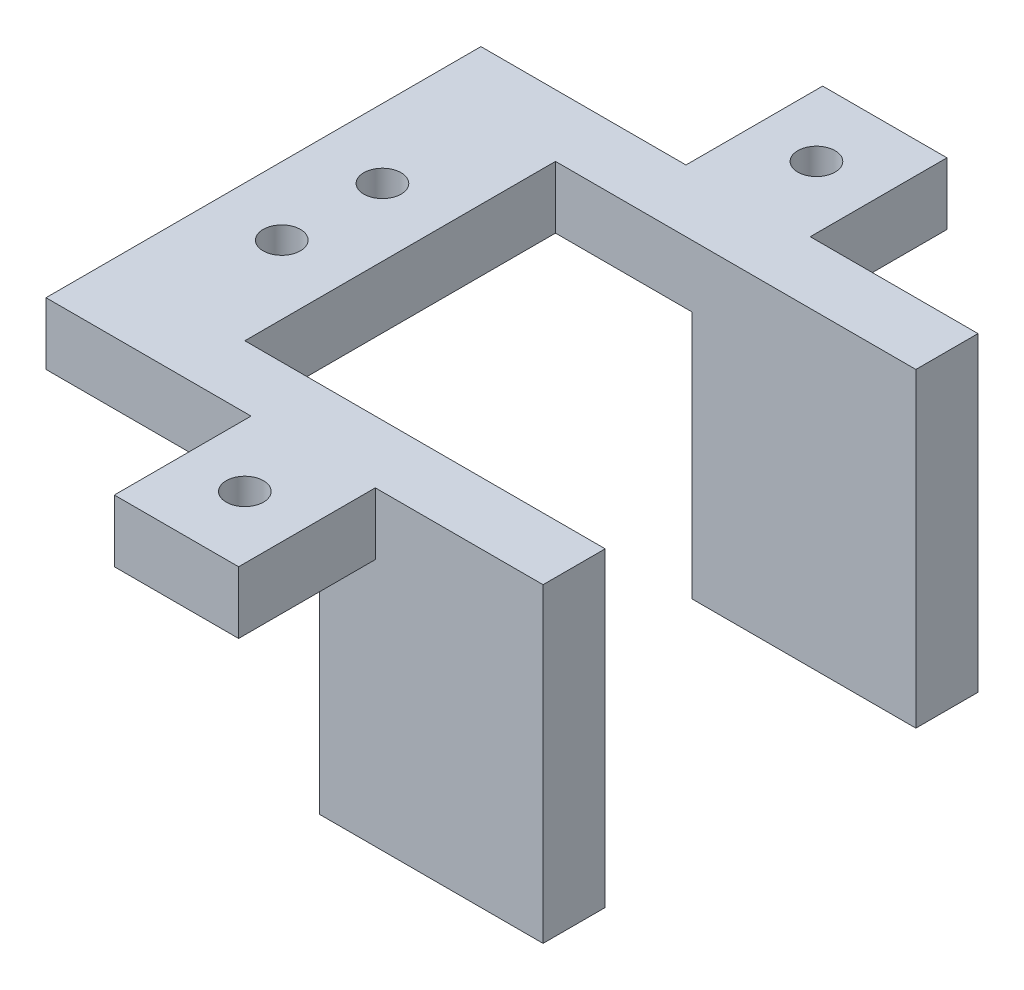
SolidWorks part; units mm, degrees
ref_plane "Front Plane" through (0, 0, 0) normal (0, 0, 1) x (1, 0, 0)
ref_plane "Top Plane" through (0, 0, 0) normal (0, 1, 0) x (1, 0, 0)
ref_plane "Right Plane" through (0, 0, 0) normal (1, 0, 0) x (0, 0, -1)
sketch "Sketch1" plane through (0, 0, 0) normal (0, 1, 0) x (1, 0, 0)
  line L0 (0, 0) -> (0, -2.5)
  line L1 (0, 0) -> (0, 2.5)
  line L3 (0, 0) -> (-1.8324, 0)
  line L5 (1.5, 3) -> (5.5, 3)
  line L6 (5.5, 3) -> (5.5, 0)
  line L7 (5.5, 0) -> (5.5, -3)
  line L8 (5.5, -3) -> (1.5, -3)
  line L10 (0, 4.5) -> (0, 8.5)
  line L11 (0, 8.5) -> (5.5, 8.5)
  line L12 (5.5, 8.5) -> (5.5, 3)
  line L13 (0, -8.5) -> (5.5, -8.5)
  line L14 (5.5, -8.5) -> (5.5, -3)
  line L15 (0, -8.5) -> (0, -4.5)
  line L16 (-1.5, -3) -> (-5.5, -3)
  line L17 (-5.5, -3) -> (-5.5, -8.5)
  line L18 (-5.5, -8.5) -> (0, -8.5)
  line L19 (-5.5, -3) -> (-5.5, 8.5)
  line L20 (-5.5, 8.5) -> (0, 8.5)
  circle A0 centre (0, 3) radius 1.5
  circle A1 centre (0, -3) radius 1.5
extrude "Boss-Extrude1" add sketch "Sketch1" along normal blind 5 contours L19 L20 L11 L12 L6 L7 L14 L13 L18 L17
sketch "Sketch3" plane through (0, 0, 8.5) normal (0, 0, 1) x (1, 0, 0)
  line L0 (-5.5, 5) -> (-5.5, 0)
  line L1 (-5.5, 0) -> (5.5, 0)
  line L2 (5.5, 0) -> (5.5, 5)
  line L3 (5.5, 5) -> (-5.5, 5)
extrude "Boss-Extrude2" add sketch "Sketch3" along normal blind 5
sketch "Sketch4" plane through (5.5, 0, 0) normal (1, 0, 0) x (0, 0, -1)
  line L0 (-13.5, 5) -> (-8.5, 5)
  line L1 (-13.5, 5) -> (8.5, 5) construction
  line L2 (-8.5, 5) -> (-8.5, 0)
  line L3 (8.5, 0) -> (-13.5, 0) construction
  line L4 (-8.5, 0) -> (-13.5, 0)
  line L5 (-13.5, 0) -> (-13.5, 5)
extrude "Boss-Extrude3" add sketch "Sketch4" along normal blind 21
sketch "Sketch5" plane through (0, 0, 0) normal (0, -1, 0) x (1, 0, 0)
  line L0 (26.5, 13.5) -> (16.5, 13.5)
  line L1 (-5.5, 13.5) -> (26.5, 13.5) construction
  line L2 (16.5, 13.5) -> (16.5, 8.5)
  line L3 (26.5, 8.5) -> (5.5, 8.5) construction
  line L4 (16.5, 8.5) -> (26.5, 8.5)
  line L5 (26.5, 8.5) -> (26.5, 13.5)
extrude "Boss-Extrude4" add sketch "Sketch5" along normal blind 20
sketch "Sketch6" plane through (0, 0, -8.5) normal (0, 0, -1) x (-1, 0, 0)
  line L0 (5.5, 5) -> (5.5, 0)
  line L1 (5.5, 0) -> (-5.5, 0)
  line L2 (-5.5, 0) -> (-5.5, 5)
  line L3 (-5.5, 5) -> (5.5, 5)
extrude "Boss-Extrude5" add sketch "Sketch6" along normal blind 5
sketch "Sketch7" plane through (5.5, 0, 0) normal (1, 0, 0) x (0, 0, -1)
  line L0 (13.5, 5) -> (8.5, 5)
  line L1 (-8.5, 5) -> (13.5, 5) construction
  line L2 (8.5, 5) -> (8.5, 0)
  line L3 (13.5, 0) -> (-8.5, 0) construction
  line L4 (8.5, 0) -> (13.5, 0)
  line L5 (13.5, 0) -> (13.5, 5)
extrude "Boss-Extrude6" add sketch "Sketch7" along normal blind 21
sketch "Sketch8" plane through (0, 0, 0) normal (0, -1, 0) x (-1, 0, 0)
  line L0 (-26.5, 8.5) -> (-16.5, 8.5)
  line L1 (-26.5, 8.5) -> (-5.5, 8.5) construction
  line L2 (-16.5, 8.5) -> (-16.5, 13.5)
  line L3 (-26.5, 13.5) -> (5.5, 13.5) construction
  line L4 (-16.5, 13.5) -> (-26.5, 13.5)
  line L5 (-26.5, 13.5) -> (-26.5, 8.5)
extrude "Boss-Extrude7" add sketch "Sketch8" along normal blind 20 contours L2 L4 L5 L0
sketch "Sketch11" plane through (0, 0, 8.5) normal (0, 0, -1) x (-1, 0, 0)
  line L0 (-26.5, -20) -> (-26.5, -15)
  line L1 (-26.5, -20) -> (-26.5, 5) construction
  line L2 (-26.5, -15) -> (-26.5, -10)
  line L3 (-26.5, -10) -> (-16.5, -10)
  line L4 (-16.5, -20) -> (-16.5, 0) construction
  line L5 (-16.5, -10) -> (-16.5, -15)
  line L6 (-16.5, -15) -> (-26.5, -15)
extrude "Boss-Extrude8" add sketch "Sketch11" along normal blind 3.5 contours L2 L3 L5 L6
sketch "Sketch12" plane through (0, 0, -8.5) normal (0, 0, 1) x (1, 0, 0)
  line L0 (26.5, -20) -> (26.5, -15)
  line L1 (26.5, 5) -> (26.5, -20) construction
  line L2 (26.5, -15) -> (26.5, -10)
  line L3 (26.5, -10) -> (16.5, -10)
  line L4 (16.5, -20) -> (16.5, 0) construction
  line L5 (16.5, -10) -> (16.5, -15)
  line L6 (16.5, -15) -> (26.5, -15)
extrude "Boss-Extrude9" add sketch "Sketch12" along normal blind 3.5 contours L2 L3 L5 L6
sketch "Sketch14" plane through (26.5, 0, 0) normal (1, 0, 0) x (0, 0, -1)
  line L4 (-6.3796, -12.8796) -> (-6.3796, -15)
  line L7 (-6.3796, -15) -> (-5, -15)
  line L8 (-6.3796, -12.8796) -> (-6.3796, -11.4398)
  line L10 (-6.3796, -11.4398) -> (-5, -11.4398)
  line L11 (-5, -15) -> (-5, -10) construction
  line L12 (-5, -15) -> (-8.5, -15) construction
  line L13 (-5, -15) -> (-5, -11.4398)
extrude "Cut-Extrude6" cut sketch "Sketch14" against normal blind 14.5 contours L4 L7 L13 L10 L8
sketch "Sketch16" plane through (26.5, 0, 0) normal (1, 0, 0) x (0, 0, -1)
  line L0 (-8.5, -15) -> (-7.4398, -15)
  line L2 (-6.3796, -15) -> (-8.5, -15) construction
  line L3 (-6.3796, -15) -> (-6.3796, -13)
  line L4 (-6.3796, -11.4398) -> (-6.3796, -15) construction
  line L5 (-6.3796, -13) -> (-8.5, -15)
extrude "Cut-Extrude8" cut sketch "Sketch16" against normal blind 14.5 and the other way through all contours L3 L5 L0
sketch "Sketch17" plane through (26.5, 0, 0) normal (1, 0, 0) x (0, 0, -1)
  line L0 (5, -10) -> (5, -11.44)
  line L1 (5, -15) -> (5, -10) construction
  line L2 (5, -11.44) -> (6.38, -11.44)
  line L3 (6.38, -11.44) -> (6.38, -15)
  line L4 (5, -15) -> (8.5, -15) construction
  line L5 (5, -11.44) -> (5, -15)
  line L6 (5, -15) -> (6.38, -15)
extrude "Cut-Extrude9" cut sketch "Sketch17" against normal blind 14.5 contours L2 L3 L6 L5
sketch "Sketch18" plane through (26.5, 0, 0) normal (1, 0, 0) x (0, 0, -1)
  line L0 (6.38, -13) -> (6.38, -15)
  line L1 (6.38, -11.44) -> (6.38, -15) construction
  line L2 (6.38, -13) -> (8.5, -15)
  line L3 (6.38, -15) -> (8.5, -15)
extrude "Cut-Extrude10" cut sketch "Sketch18" against normal blind 14.5 contours L2 L3 L0
sketch "草图1" plane through (0, 0, 13.5) normal (0, 0, 1) x (1, 0, 0)
  line L0 (26.5, 5) -> (34.5, 5)
  line L1 (26.5, 5) -> (26.5, -20)
  line L2 (26.5, -20) -> (34.5, -20)
  line L3 (34.5, -20) -> (34.5, 5)
extrude "凸台-拉伸1" add sketch "草图1" against normal blind 5
sketch "草图2" plane through (0, 0, -13.5) normal (0, 0, -1) x (-1, 0, 0)
  line L0 (-26.5, -20) -> (-34.5, -20)
  line L1 (-34.5, -20) -> (-34.5, 5)
  line L2 (-34.5, 5) -> (-26.5, 5)
  line L3 (-26.5, 5) -> (-26.5, -20)
extrude "凸台-拉伸2" add sketch "草图2" against normal blind 5
sketch "草图3" plane through (0, 0, 13.5) normal (0, 0, 1) x (1, 0, 0)
  line L0 (16.5, -20) -> (16.5, -15)
sketch "草图4" plane through (0, 0, 8.5) normal (0, 0, -1) x (-1, 0, 0)
  line L7 (-22.5, 5) -> (-22.5, 0.9274) construction
  line L8 (-22.5, 5) -> (-22.5, 3.9274) construction
  line L9 (-22.5, 3.9274) -> (-22.5, 3.0274)
  line L10 (-5.5, 5) -> (-34.5, 5)
  line L11 (-34.5, 5) -> (-34.5, -20)
  line L12 (-34.5, -20) -> (-16.5, -20)
  line L13 (-16.5, -20) -> (-16.5, -15)
  line L14 (-16.5, -15) -> (-26.5, -15)
  line L15 (-26.5, -15) -> (-26.5, -10)
  line L16 (-26.5, -10) -> (-16.5, -10)
  line L17 (-16.5, -10) -> (-16.5, 0)
  line L18 (-16.5, 0) -> (-5.5, 0)
  line L19 (-5.5, 0) -> (-5.5, 5)
  line L20 (-5.5, 5) -> (-34.5, 5) construction
  line L21 (-34.5, 5) -> (-34.5, -20) construction
  line L22 (-34.5, -20) -> (-16.5, -20) construction
  line L23 (-16.5, -20) -> (-16.5, -15) construction
  line L24 (-16.5, -15) -> (-26.5, -15) construction
  line L25 (-26.5, -15) -> (-26.5, -10) construction
  line L26 (-26.5, -10) -> (-16.5, -10) construction
  line L27 (-16.5, -10) -> (-16.5, 0) construction
  line L28 (-16.5, 0) -> (-5.5, 0) construction
  line L29 (-5.5, 0) -> (-5.5, 5) construction
  line L30 (-23.4, 3.0274) -> (-23.4, 0.0274)
  line L31 (-23.4, 0.0274) -> (-22.5, 0.0274)
  line L32 (-21.6, 0.0274) -> (-21.6, 3.0274)
  line L33 (-22.5, 0.0274) -> (-22.5, -9.8364) construction
  arc A0 (-21.6, 3.0274) -> (-23.4, 3.0274) centre (-22.5, 3.0274) ccw
  arc A1 (-23.4, 0.0274) -> (-21.6, 0.0274) centre (-22.5, 0.0274) ccw
  dimension "D1" = 0
sketch "草图6" plane through (0, 0, -8.5) normal (0, 0, 1) x (1, 0, 0)
  line L5 (21.5, 3.1) -> (21.5, 0.1)
  line L6 (23.3, 3.1) -> (23.3, 0.1)
  line L10 (16.5, -10) -> (26.5, -10)
  line L11 (26.5, -10) -> (26.5, -15)
  line L14 (26.5, -15) -> (16.5, -15)
  line L15 (26.5, -15) -> (16.5, -15)
  line L16 (34.5, 5) -> (5.5, 5)
  line L17 (5.5, 5) -> (5.5, 0)
  line L18 (5.5, 0) -> (16.5, 0)
  line L19 (16.5, 0) -> (16.5, -10)
  line L20 (16.5, -10) -> (26.5, -10) construction
  line L21 (26.5, -10) -> (26.5, -15) construction
  line L26 (34.5, 5) -> (5.5, 5) construction
  line L27 (5.5, 5) -> (5.5, 0) construction
  line L28 (5.5, 0) -> (16.5, 0) construction
  line L29 (16.5, 0) -> (16.5, -10) construction
  line L30 (16.5, -15) -> (16.5, -20)
  line L31 (16.5, -15) -> (16.5, -20)
  line L32 (16.5, -20) -> (34.5, -20)
  line L33 (16.5, -20) -> (34.5, -20)
  line L34 (34.5, -20) -> (34.5, 5)
  line L35 (34.5, -20) -> (34.5, 5)
  arc A1 (23.3, 3.1) -> (21.5, 3.1) centre (22.4, 3.1) ccw
  arc A2 (21.5, 0.1) -> (23.3, 0.1) centre (22.4, 0.1) ccw
  dimension "D1" = 0
sketch "Skizze1" plane through (0, 5, 0) normal (0, 1, 0) x (1, 0, 0)
  line L0 (0, 13.5) -> (0, 5.5)
  line L2 (-5.5, 13.5) -> (34.5, 13.5) construction
  line L3 (0, -13.5) -> (0, -5.5)
  line L4 (34.5, -13.5) -> (-5.5, -13.5) construction
  circle A0 centre (-0.0269, -4.0002) radius 1.5
  circle A1 centre (0.0725, 4.0018) radius 1.5
extrude "Schnitt-Linear austragen1" cut sketch "Skizze1" against normal blind 10 contours A0 | A1
sketch "Skizze2" plane through (0, 0, 13.5) normal (0, 0, 1) x (1, 0, 0)
  line L0 (-5.5, 5) -> (-5.5, 0)
  line L1 (-5.5, 0) -> (16.5, 0)
  line L2 (16.5, 0) -> (16.5, -20)
  line L3 (16.5, -20) -> (34.5, -20)
  line L4 (34.5, -20) -> (34.5, 5)
  line L5 (34.5, 5) -> (-5.5, 5)
extrude "Aufsatz-Linear austragen1" add sketch "Skizze2" along normal blind 4
sketch "Skizze3" plane through (0, 0, 5) normal (0, 0, -1) x (-1, 0, 0)
  line L0 (-26.5, -10) -> (-26.5, -15)
  line L1 (-26.5, -15) -> (-16.5, -15)
  line L2 (-16.5, -15) -> (-16.5, -10)
  line L3 (-16.5, -10) -> (-26.5, -10)
extrude "Schnitt-Linear austragen2" cut sketch "Skizze3" against normal blind 3.5
sketch "Skizze4" plane through (0, 0, 8.5) normal (0, 0, -1) x (-1, 0, 0)
  line L0 (-34.5, 5) -> (-34.5, -20)
  line L1 (-34.5, -20) -> (-16.5, -20)
  line L2 (-16.5, -20) -> (-16.5, 0)
  line L3 (-16.5, 0) -> (-5.5, 0)
  line L4 (-5.5, 0) -> (-5.5, 5)
  line L5 (-5.5, 5) -> (-34.5, 5)
extrude "Schnitt-Linear austragen3" cut sketch "Skizze4" against normal blind 4
sketch "Skizze6" plane through (0, 0, 17.5) normal (0, 0, 1) x (1, 0, 0)
  line L0 (-5.5, 5) -> (5.5, 5)
  line L1 (34.5, 5) -> (-5.5, 5) construction
  line L2 (11, 5) -> (21, 5)
  line L3 (16, 5) -> (11, 5)
  line L4 (16, 5) -> (21, 5)
  line L5 (11, 5) -> (11, 0)
  line L6 (-5.5, 0) -> (16.5, 0) construction
  line L7 (11, 0) -> (21, 0)
  line L8 (21, 0) -> (21, 5)
  line M1 (34.5, 5) -> (-5.5, 5)
  line M3 (-5.5, 0) -> (16.5, 0)
extrude "Aufsatz-Linear austragen3" add sketch "Skizze6" along normal blind 11 contours L7 L8 L2 L5 M1 M3
sketch "Skizze7" plane through (0, 5, 0) normal (0, 1, 0) x (1, 0, 0)
  circle A0 centre (16, -23) radius 1.5
  circle A1 centre (16, -23) radius 3.5
extrude "Schnitt-Linear austragen6" cut sketch "Skizze7" against normal blind 10 contours A0
sketch "Skizze8" plane through (0, 0, -8.5) normal (0, 0, 1) x (1, 0, 0)
  line L0 (16.5, -10) -> (16.5, -15)
  line L1 (16.5, -15) -> (26.5, -15)
  line L2 (26.5, -15) -> (26.5, -10)
  line L3 (26.5, -10) -> (16.5, -10)
extrude "Schnitt-Linear austragen8" cut sketch "Skizze8" along normal blind 4
sketch "Skizze9" plane through (0, 0, -13.5) normal (0, 0, -1) x (-1, 0, 0)
  line L0 (-34.5, 5) -> (-34.5, -20)
  line L1 (-34.5, -20) -> (-16.5, -20)
  line L2 (-16.5, -20) -> (-16.5, 0)
  line L3 (-16.5, 0) -> (5.5, 0)
  line L4 (5.5, 0) -> (5.5, 5)
  line L5 (5.5, 5) -> (-34.5, 5)
extrude "Aufsatz-Linear austragen4" add sketch "Skizze9" along normal blind 4
sketch "Skizze10" plane through (0, 0, -8.5) normal (0, 0, 1) x (1, 0, 0)
  line L0 (5.5, 5) -> (5.5, 0)
  line L1 (5.5, 0) -> (16.5, 0)
  line L2 (16.5, 0) -> (16.5, -20)
  line L3 (16.5, -20) -> (34.5, -20)
  line L4 (34.5, -20) -> (34.5, 5)
  line L5 (34.5, 5) -> (5.5, 5)
extrude "Schnitt-Linear austragen9" cut sketch "Skizze10" against normal blind 4
sketch "Skizze11" plane through (0, 0, -17.5) normal (0, 0, -1) x (-1, 0, 0)
  line L0 (5.5, 5) -> (-6.249, 5)
  line L1 (5.5, 5) -> (-34.5, 5) construction
  line L2 (-11, 5) -> (-21, 5)
  line L12 (5.5, 5) -> (-11, 5)
  line L13 (-21, 5) -> (-21, 0)
  line L14 (-21, 0) -> (-11, 0)
  line L15 (-11, 0) -> (-11, 5)
  line M1 (5.5, 5) -> (-34.5, 5)
  line M5 (-16.5, 0) -> (5.5, 0)
extrude "Aufsatz-Linear austragen6" add sketch "Skizze11" along normal blind 11 contours L15 L13 L14 M5 M1
sketch "Skizze12" plane through (0, 5, 0) normal (0, 1, 0) x (1, 0, 0)
  circle A0 centre (16, 23) radius 1.5
  circle A1 centre (16, 23) radius 3.5
extrude "Schnitt-Linear austragen10" cut sketch "Skizze12" against normal blind 11 contours A0
